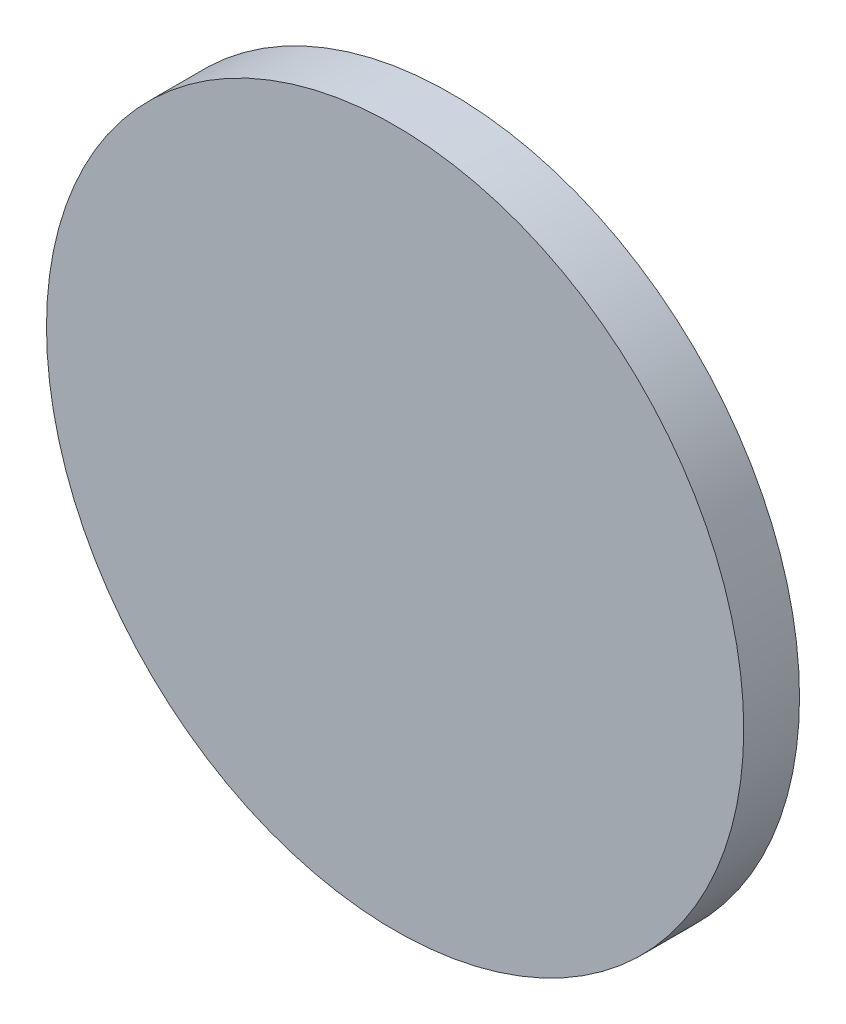
SolidWorks part; units mm, degrees
material "玻璃"
ref_plane "前视基准面" through (0, 0, 0) normal (0, 0, 1) x (1, 0, 0)
ref_plane "上视基准面" through (0, 0, 0) normal (0, 1, 0) x (1, 0, 0)
ref_plane "右视基准面" through (0, 0, 0) normal (1, 0, 0) x (0, 0, -1)
sketch "草图1" plane through (0, 0, 0) normal (0, 0, 1) x (1, 0, 0)
  circle A0 centre (0, 0) radius 12.5
  dimension "D1" = 25
extrude "凸台-拉伸1" add sketch "草图1" along normal blind 2
